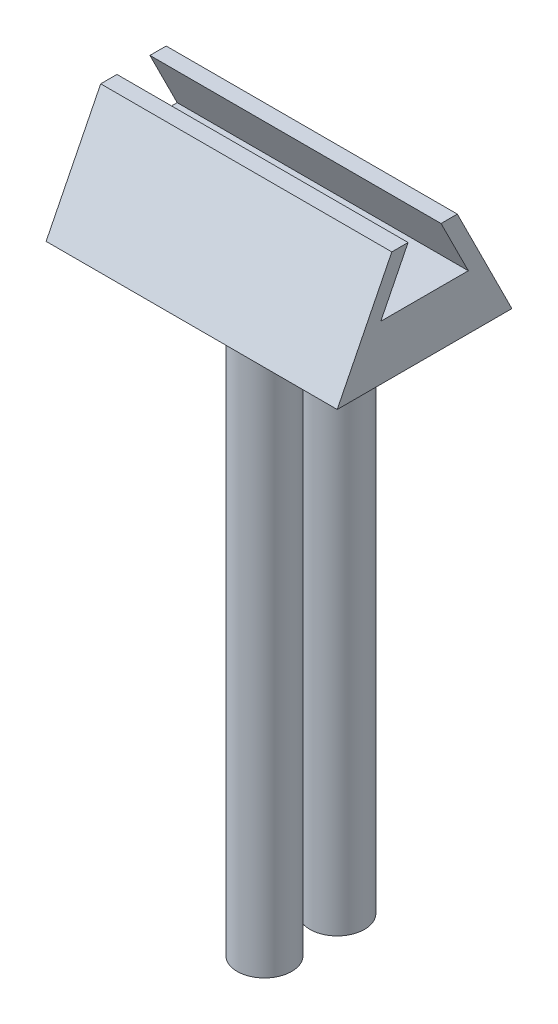
SolidWorks part; units mm, degrees
ref_plane "Front Plane" through (0, 0, 0) normal (0, 0, 1) x (1, 0, 0)
ref_plane "Top Plane" through (0, 0, 0) normal (0, 1, 0) x (1, 0, 0)
ref_plane "Right Plane" through (0, 0, 0) normal (1, 0, 0) x (0, 0, -1)
sketch "Sketch1" plane through (0, 0, 0) normal (0, 1, 0) x (1, 0, 0)
  line L1 (0, 0) -> (-80, 0)
  line L2 (0, 0) -> (0, 48)
  line L3 (0, 48) -> (-80, 48)
  line L4 (-80, 0) -> (-80, 48)
  dimension "D1" = 48
  dimension "D2" = 80
extrude "Boss-Extrude1" add sketch "Sketch1" along normal blind 30
sketch "Sketch2" plane through (0, 0, 0) normal (1, 0, 0) x (0, 0, -1)
  line L0 (0, 0) -> (15, 30)
  line L1 (0, 30) -> (48, 30) construction
  line L2 (15, 30) -> (0, 30)
  line L3 (0, 30) -> (0, 0)
  line L4 (48, 0) -> (33, 30)
  line L5 (33, 30) -> (48, 30)
  line L6 (48, 30) -> (48, 0)
  dimension "D1" = 15
  dimension "D2" = 15
extrude "Cut-Extrude1" cut sketch "Sketch2" against normal through all
sketch "Sketch3" plane through (0, 0, 0) normal (1, 0, 0) x (0, 0, -1)
  line L0 (19.4721, 30) -> (11.9721, 15)
  line L1 (15, 30) -> (33, 30) construction
  line L2 (11.9721, 15) -> (36.0279, 15)
  line L3 (36.0279, 15) -> (28.5279, 30)
  line L4 (28.5279, 30) -> (19.4721, 30)
  line L5 (33, 30) -> (48, 0) construction
  line L6 (0, 0) -> (15, 30) construction
  point P10 (14.871, 20.9393)
  point P11 (12.0166, 15.089)
  dimension "D1" = 4
  dimension "D2" = 4
  dimension "D3" = 15
extrude "Cut-Extrude2" cut sketch "Sketch3" against normal through all
sketch "Sketch4" plane through (0, 0, 0) normal (0, -1, 0) x (1, 0, 0)
  line L0 (-80, 0) -> (0, 0) construction
  line L1 (0, 0) -> (0, -48) construction
  circle A0 centre (-40, -20) radius 7.5
  circle A1 centre (-40, -40) radius 7.5
  point P8 (0, 0)
  dimension "D1" = 15
  dimension "D2" = 15
  dimension "D3" = 20
  dimension "D4" = 40
  dimension "D5" = 40
  dimension "D6" = 40
extrude "Boss-Extrude2" add sketch "Sketch4" along normal blind 160
